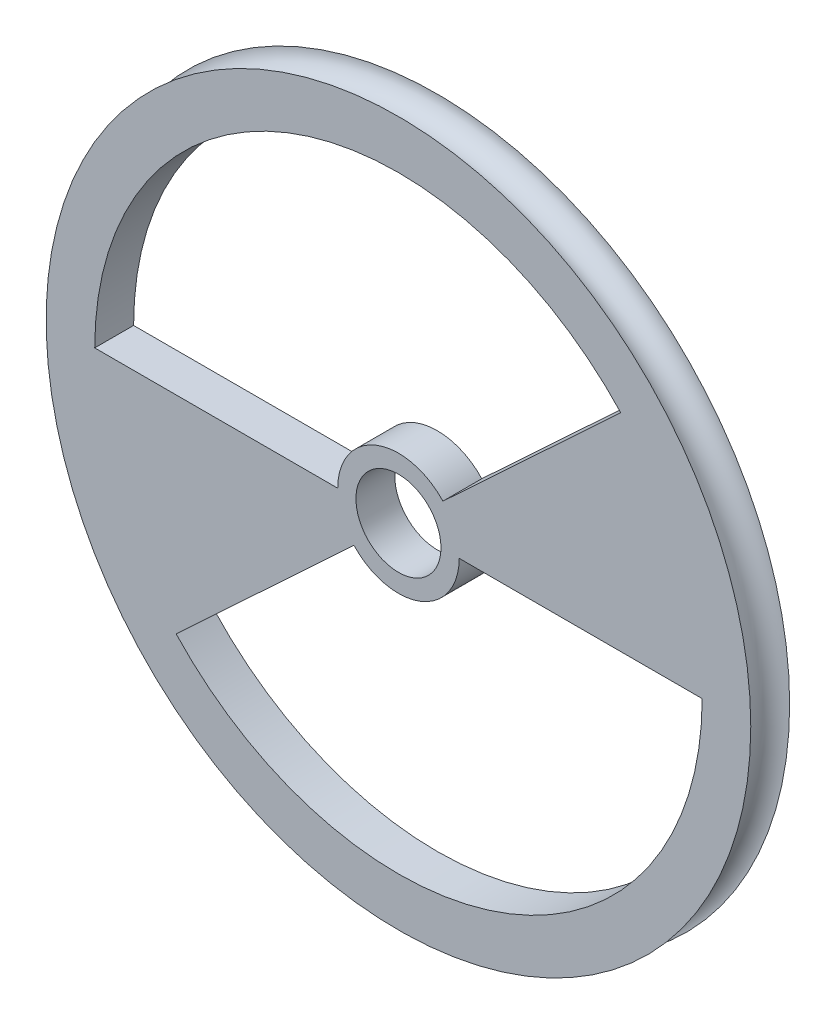
SolidWorks part; units mm, degrees
ref_plane "Front Plane" through (0, 0, 0) normal (0, 0, 1) x (1, 0, 0)
ref_plane "Top Plane" through (0, 0, 0) normal (0, 1, 0) x (1, 0, 0)
ref_plane "Right Plane" through (0, 0, 0) normal (1, 0, 0) x (0, 0, -1)
sketch "Sketch1" plane through (0, 0, 0) normal (0, 0, 1) x (1, 0, 0)
  line L0 (-5, 0) -> (-25, 0)
  line L1 (-3.66, -3.4066) -> (-18.2999, -17.0328)
  line L2 (5, 0) -> (25, 0)
  line L4 (3.66, 3.4066) -> (18.2999, 17.0328)
  circle A0 centre (0, 0) radius 29
  circle A1 centre (0, 0) radius 25
  circle A2 centre (0, 0) radius 3.5
  circle A3 centre (0, 0) radius 5
  dimension "D1" = 58
  dimension "D2" = 4
  dimension "D3" = 7
  dimension "D4" = 10
extrude "Boss-Extrude3" add sketch "Sketch1" along normal blind 3.2 contours A3 L0 A1 L1 | A3 L2 A1 L4 | A0 A1 | A3 A2
sketch "Sketch6" plane through (0, 0, 0) normal (1, 0, 0) x (0, 0, -1)
  line L0 (-3.2, 29) -> (-3.2, -29) construction
  line L1 (0, 29) -> (-3.2, 29)
  arc A0 (0, 29) -> (-3.2, 29) centre (-1.6, 29) cw
  dimension "D1" = 3.2
sketch "Sketch10" plane through (0, 0, 0) normal (1, 0, 0) x (0, 0, -1)
  line L0 (-3.2, 0) -> (0, 0)
  line L2 (-3.2, 29) -> (-3.2, -29) construction
  dimension "D1" = 3.2
revolve "Cut-Revolve4" cut sketch "Sketch6" angle 360 about L0
